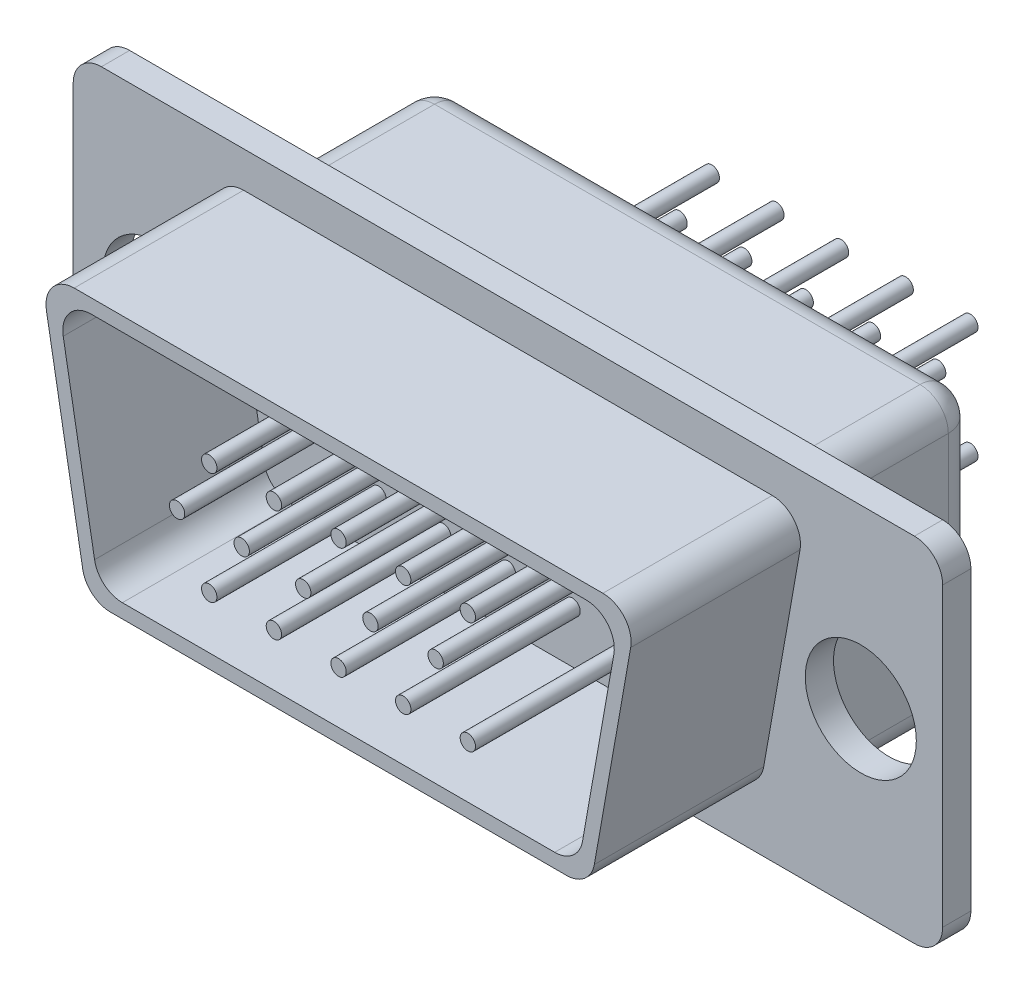
SolidWorks part; units mm, degrees
ref_plane "Plan de face" through (0, 0, 0) normal (0, 0, 1) x (1, 0, 0)
ref_plane "Plan de dessus" through (0, 0, 0) normal (0, 1, 0) x (1, 0, 0)
ref_plane "Plan de droite" through (0, 0, 0) normal (1, 0, 0) x (0, 0, -1)
sketch "Esquisse1" plane through (0, 0, 0) normal (0, 0, 1) x (1, 0, 0)
  line L0 (0, 0) -> (30.8, 12.5) construction
  line L1 (0, 0) -> (30.8, 0)
  line L2 (0, 0) -> (0, 12.5)
  line L3 (0, 12.5) -> (30.8, 12.5)
  line L4 (30.8, 0) -> (30.8, 12.5)
  line L5 (27.9, 6.25) -> (2.9, 6.25) construction
  line L6 (0, 12.5) -> (30.8, 0) construction
  circle A0 centre (2.9, 6.25) radius 1.8473
  circle A1 centre (27.9, 6.25) radius 1.9669
  point P9 (15.4, 6.25)
  dimension "D1" = 30.8
  dimension "D2" = 12.5
  dimension "D3" = 25
extrude "Extrusion1" add sketch "Esquisse1" along normal blind 1
sketch "Esquisse2" plane through (0, 0, 1) normal (0, 0, 1) x (1, 0, 0)
  line L0 (6.6318, 10.7291) -> (24.1682, 10.7291)
  line L1 (25.1531, 9.5554) -> (24.0422, 3.2554)
  line L2 (23.0574, 2.4291) -> (7.7426, 2.4291)
  line L3 (6.7578, 3.2554) -> (5.6469, 9.5554)
  line L4 (0, 0) -> (30.8, 12.5) construction
  line L5 (30.8, 0) -> (30.8, 12.5) construction
  line L6 (0, 12.5) -> (30.8, 0) construction
  line L7 (5.44, 10.7291) -> (23.8965, 2.4291) construction
  line L8 (25.36, 10.7291) -> (6.9035, 2.4291) construction
  line L9 (6.0359, 11.2291) -> (24.7641, 11.2291)
  line L10 (25.7489, 10.0554) -> (24.4617, 2.7554)
  line L11 (23.4769, 1.9291) -> (7.3231, 1.9291)
  line L12 (6.3383, 2.7554) -> (5.0511, 10.0554)
  arc A0 (5.6469, 9.5554) -> (6.6318, 10.7291) centre (6.6318, 9.7291) cw
  arc A1 (5.0511, 10.0554) -> (6.0359, 11.2291) centre (6.0359, 10.2291) cw
  arc A2 (25.7489, 10.0554) -> (24.7641, 11.2291) centre (24.7641, 10.2291) ccw
  arc A3 (25.1531, 9.5554) -> (24.1682, 10.7291) centre (24.1682, 9.7291) ccw
  arc A4 (24.0422, 3.2554) -> (23.0574, 2.4291) centre (23.0574, 3.4291) cw
  arc A5 (23.4769, 1.9291) -> (24.4617, 2.7554) centre (23.4769, 2.9291) ccw
  arc A6 (7.7426, 2.4291) -> (6.7578, 3.2554) centre (7.7426, 3.4291) cw
  arc A7 (6.3383, 2.7554) -> (7.3231, 1.9291) centre (7.3231, 2.9291) ccw
  point P13 (15.4, 6.25)
  point P14 (15.4, 6.25)
  dimension "D9" = 1
  dimension "D1" = 19.92
  dimension "D2" = 100
  dimension "D3" = 100
  dimension "D4" = 8.3
  dimension "D5" = 0.5
  dimension "D6" = 0.5
  dimension "D7" = 0.5
  dimension "D8" = 0.5
extrude "Extrusion2" add sketch "Esquisse2" along normal blind 6
sketch "Esquisse3" plane through (0, 0, 0) normal (0, 0, -1) x (-1, 0, 0)
  line L0 (-25, 1.25) -> (-5.8, 11.25) construction
  line L1 (-25, 11.25) -> (-5.8, 11.25)
  line L2 (-25, 11.25) -> (-25, 1.25)
  line L3 (-25, 1.25) -> (-5.8, 1.25)
  line L4 (-5.8, 11.25) -> (-5.8, 1.25)
  line L5 (-5.8, 1.25) -> (-25, 11.25) construction
  line L6 (-30.8, 12.5) -> (0, 0) construction
  line L8 (0, 12.5) -> (-30.8, 0) construction
  point P8 (-15.4, 6.25)
  point P13 (-15.4, 6.25)
  dimension "D1" = 19.2
  dimension "D2" = 10
extrude "Extrusion3" add sketch "Esquisse3" along normal blind 6
sketch "Esquisse4" plane through (0, 0, -6) normal (0, 0, -1) x (-1, 0, 0)
  line L0 (-19.98, 8.23) -> (-10.82, 8.23) construction
  line L1 (-10.82, 8.23) -> (-9.544, 6.0138) construction
  line L2 (-10.82, 4.27) -> (-19.98, 4.27) construction
  line L3 (-19.98, 8.23) -> (-19.98, 4.27) construction
  line L4 (-17.69, 8.23) -> (-16.3999, 5.9892) construction
  line L5 (-15.4, 8.23) -> (-14.0179, 5.8295) construction
  line L6 (-13.11, 8.23) -> (-11.834, 6.0138) construction
  line L7 (-18.84, 6.25) -> (-9.68, 6.25) construction
  line L8 (-18.84, 6.25) -> (-19.98, 8.23) construction
  line L9 (-17.69, 4.27) -> (-17.69, 8.23) construction
  line L10 (-15.4, 8.23) -> (-15.4, 4.27) construction
  line L11 (-13.11, 8.23) -> (-13.11, 4.27) construction
  line L12 (-10.82, 4.27) -> (-10.82, 8.23) construction
  line L13 (-25, 1.25) -> (-5.8, 11.25) construction
  line L14 (-25, 11.25) -> (-5.8, 1.25) construction
  circle A0 centre (-19.98, 8.23) radius 0.2725
  circle A1 centre (-17.69, 8.23) radius 0.2725
  circle A2 centre (-15.4, 8.23) radius 0.2725
  circle A3 centre (-13.11, 8.23) radius 0.2725
  circle A4 centre (-10.82, 8.23) radius 0.2725
  circle A5 centre (-9.68, 6.25) radius 0.2725
  circle A6 centre (-11.97, 6.25) radius 0.2725
  circle A7 centre (-14.1497, 6.0681) radius 0.2725
  circle A8 centre (-16.5297, 6.2288) radius 0.2725
  circle A9 centre (-18.84, 6.25) radius 0.2725
  circle A10 centre (-19.98, 4.27) radius 0.2725
  circle A11 centre (-17.69, 4.27) radius 0.2725
  circle A12 centre (-15.4, 4.27) radius 0.2725
  circle A13 centre (-13.11, 4.27) radius 0.2725
  circle A14 centre (-10.82, 4.27) radius 0.2725
  point P13 (-16.55, 6.25)
  point P14 (-14.26, 6.25)
  point P15 (-11.97, 6.25)
  point P39 (-15.4, 6.25)
  dimension "D1" = 2.29
  dimension "D2" = 2.29
  dimension "D3" = 2.29
  dimension "D4" = 2.29
  dimension "D5" = 1.98
  dimension "D6" = 1.98
  dimension "D7" = 1.14
extrude "Extrusion4" add sketch "Esquisse4" along normal blind 4.8
fillet "Congé1" radius 1 12 edges at (15.4, 1.25, -6) (5.8, 6.25, -6) (5.8, 1.25, -3) (5.8, 11.25, -3) (15.4, 11.25, -6) (25, 11.25, -3) (25, 6.25, -6) (25, 1.25, -3) (30.8, 0, 0.5) (30.8, 12.5, 0.5) (0, 0, 0.5) (0, 12.5, 0.5)
sketch "Esquisse7" plane through (0, 0, 1) normal (0, 0, 1) x (1, 0, 0)
  circle A0 centre (19.98, 8.23) radius 0.2725
  circle A1 centre (17.69, 8.23) radius 0.2725
  circle A2 centre (15.4, 8.23) radius 0.2725
  circle A3 centre (13.11, 8.23) radius 0.2725
  circle A4 centre (10.82, 8.23) radius 0.2725
  circle A5 centre (9.68, 6.25) radius 0.2725
  circle A6 centre (11.97, 6.25) radius 0.2725
  circle A7 centre (14.1497, 6.0681) radius 0.2725
  circle A8 centre (16.5297, 6.2288) radius 0.2725
  circle A9 centre (18.84, 6.25) radius 0.2725
  circle A10 centre (19.98, 4.27) radius 0.2725
  circle A11 centre (17.69, 4.27) radius 0.2725
  circle A12 centre (15.4, 4.27) radius 0.2725
  circle A13 centre (13.11, 4.27) radius 0.2725
  circle A14 centre (10.82, 4.27) radius 0.2725
extrude "Extrusion6" add sketch "Esquisse7" along normal up to surface (6 mm away) up to face at (15.4, 6.5048, 7)
